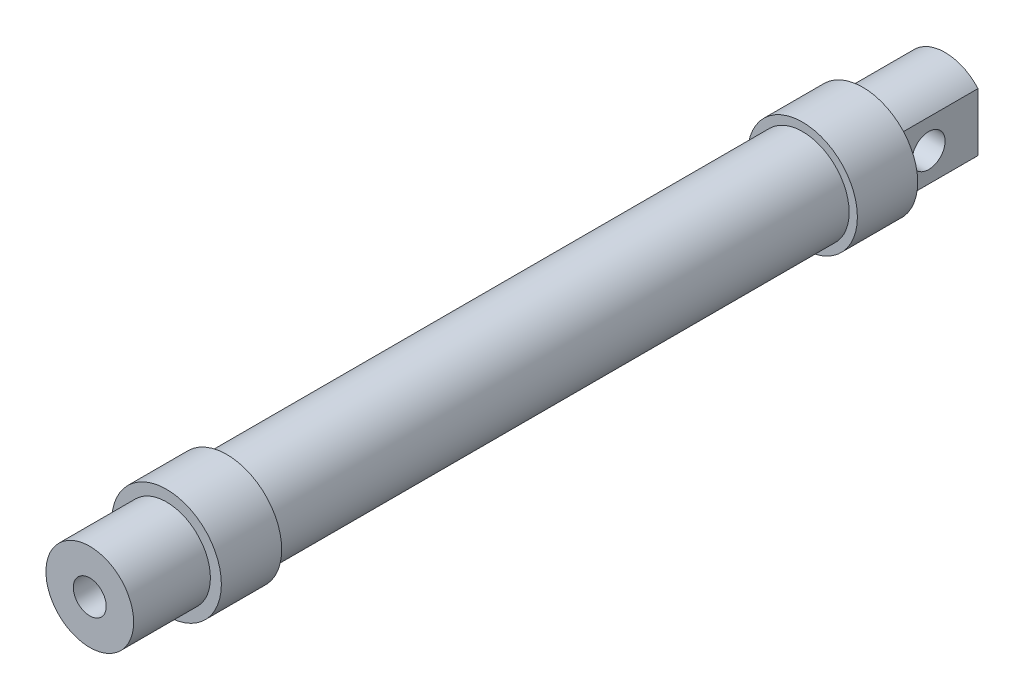
SolidWorks part; units mm, degrees
material "6061 合金"
ref_plane "前视基准面" through (0, 0, 0) normal (0, 0, 1) x (1, 0, 0)
ref_plane "上视基准面" through (0, 0, 0) normal (0, 1, 0) x (1, 0, 0)
ref_plane "右视基准面" through (0, 0, 0) normal (1, 0, 0) x (0, 0, -1)
sketch "草图1" plane through (0, 0, 0) normal (0, 0, 1) x (1, 0, 0)
  line L0 (-6, 5.2915) -> (-6, -5.2915)
  line L1 (0, 8) -> (0, -8) construction
  line L2 (6, 5.2915) -> (6, -5.2915)
  circle A0 centre (0, 0) radius 8
  dimension "D1" = 16
  dimension "D2" = 6
extrude "凸台-拉伸1" add sketch "草图1" along normal blind 15 contours L1 A0 L0 | A0 L1 L2
cosmetic thread "装饰螺纹线4" parameters "D2"=14.344
cosmetic thread "装饰螺纹线5" parameters "D2"=14.344
sketch "草图2" plane through (-6, 0, 0) normal (-1, 0, 0) x (0, 0, 1)
  line L0 (15, 0) -> (0, 0) construction
  line L1 (15, 5.2915) -> (15, -5.2915) construction
  circle A0 centre (9, 0) radius 3
  dimension "D1" = 6
  dimension "D2" = 6
extrude "切除-拉伸1" cut sketch "草图2" against normal through all
sketch "草图3" plane through (0, 0, 15) normal (0, 0, 1) x (1, 0, 0)
  circle A0 centre (0, 0) radius 10
  dimension "D1" = 20
extrude "凸台-拉伸2" add sketch "草图3" along normal blind 11
sketch "草图4" plane through (0, 0, 0) normal (0, 1, 0) x (1, 0, 0)
  line L0 (0, -26) -> (0, -15) construction
  line L1 (-10, -26) -> (10, -26) construction
  line L2 (6, -15) -> (-6, -15) construction
  circle A0 centre (0, -20.5) radius 2.5
  point P6 (0, -20.5)
  dimension "D1" = 5
extrude "切除-拉伸3" cut sketch "草图4" against normal blind 10
sketch "草图5" plane through (0, 0, 26) normal (0, 0, 1) x (1, 0, 0)
  circle A0 centre (0, 0) radius 8.5
  circle A1 centre (0, 0) radius 8
  dimension "D1" = 17
  dimension "D2" = 16
extrude "凸台-拉伸4" add sketch "草图5" along normal blind 105
sketch "草图6" plane through (0, 0, 131) normal (0, 0, 1) x (1, 0, 0)
  circle A0 centre (0, 0) radius 10
  dimension "D1" = 20
extrude "凸台-拉伸5" add sketch "草图6" along normal blind 11
sketch "草图7" plane through (0, 0, 0) normal (0, 1, 0) x (1, 0, 0)
  line L0 (0, -131) -> (0, -142) construction
  line L1 (10, -131) -> (-10, -131) construction
  line L2 (-10, -142) -> (10, -142) construction
  circle A0 centre (0, -136.5) radius 2.5
  dimension "D1" = 5
extrude "切除-拉伸4" cut sketch "草图7" against normal blind 10
sketch "草图8" plane through (0, 0, 142) normal (0, 0, 1) x (1, 0, 0)
  circle A0 centre (0, 0) radius 8
  dimension "D1" = 16
extrude "凸台-拉伸6" add sketch "草图8" along normal blind 14
cosmetic thread "装饰螺纹线6" parameters "D2"=14.344
sketch "草图9" plane through (0, 0, 156) normal (0, 0, 1) x (1, 0, 0)
  circle A0 centre (0, 0) radius 3
  dimension "D1" = 6
extrude "切除-拉伸5" cut sketch "草图9" against normal blind 100
